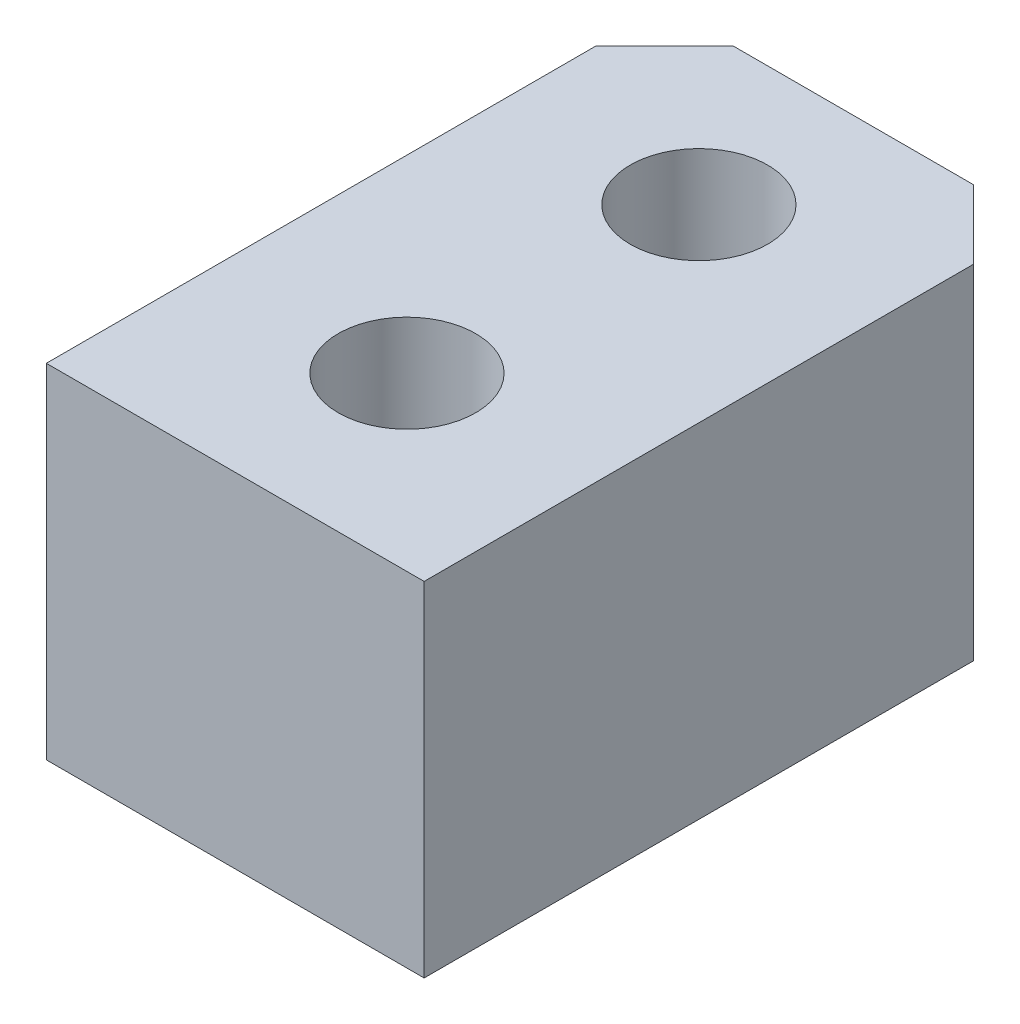
SolidWorks part; units mm, degrees
ref_plane "前视基准面" through (0, 0, 0) normal (0, 0, 1) x (1, 0, 0)
ref_plane "上视基准面" through (0, 0, 0) normal (0, 1, 0) x (1, 0, 0)
ref_plane "右视基准面" through (0, 0, 0) normal (1, 0, 0) x (0, 0, -1)
sketch "草图1" plane through (0, 0, 0) normal (0, 1, 0) x (1, 0, 0)
  line L0 (0.1158, -17.6) -> (0.1158, -7.6) construction
  line L1 (-10.8842, 18.4) -> (11.1158, 18.4)
  line L2 (-10.8842, 18.4) -> (-10.8842, -17.6)
  line L3 (-10.8842, -17.6) -> (11.1158, -17.6)
  line L4 (11.1158, 18.4) -> (11.1158, -17.6)
  line L5 (0.1158, -7.6) -> (0.1158, 9.4) construction
  circle A0 centre (0.1158, -7.6) radius 4
  circle A1 centre (0.1158, 9.4) radius 4
  dimension "D4" = 8
  dimension "D5" = 8
  dimension "D1" = 22
  dimension "D2" = 36
  dimension "D3" = 10
  dimension "D6" = 17
extrude "凸台-拉伸1" add sketch "草图1" along normal blind 20
chamfer "倒角1" distance 4 angle 45 2 edges at (-10.8842, 10, -18.4) (11.1158, 10, -18.4)
